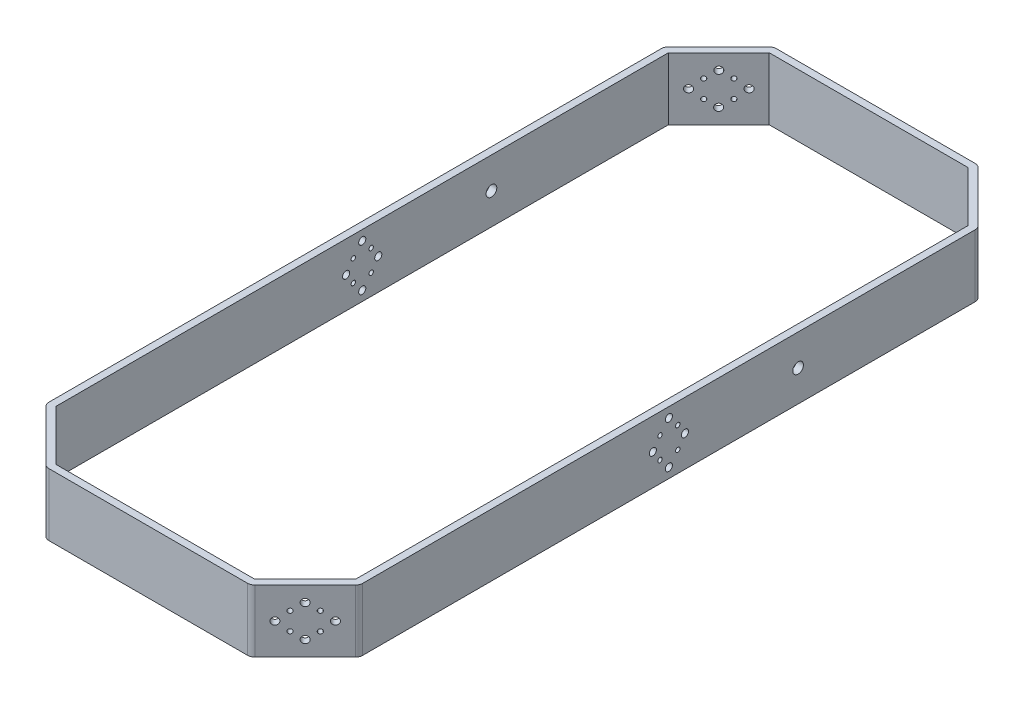
SolidWorks part; units mm, degrees
ref_plane "Ön Düzlem" through (0, 0, 0) normal (0, 0, 1) x (1, 0, 0)
ref_plane "Üst Düzlem" through (0, 0, 0) normal (0, 1, 0) x (1, 0, 0)
ref_plane "Sağ Düzlem" through (0, 0, 0) normal (1, 0, 0) x (0, 0, -1)
sketch "Çizim1" plane through (0, 0, 0) normal (0, 1, 0) x (1, 0, 0)
  line L1 (28.2843, 0) -> (139.7157, 0)
  line L2 (0, 28.2843) -> (0, 371.7157)
  line L3 (28.2843, 400) -> (139.7157, 400)
  line L4 (168, 28.2843) -> (168, 371.7157)
  line L5 (28.2843, 0) -> (0, 28.2843)
  line L6 (0, 371.7157) -> (28.2843, 400)
  line L7 (139.7157, 400) -> (168, 371.7157)
  line L8 (139.7157, 0) -> (168, 28.2843)
  line L9 (142.5442, -2.8284) -> (170.8284, 25.4558)
  line L12 (172, 28.2843) -> (172, 371.7157)
  line L15 (170.8284, 374.5442) -> (142.5442, 402.8284)
  line L18 (139.7157, 404) -> (28.2843, 404)
  line L21 (25.4558, 402.8284) -> (-2.8284, 374.5442)
  line L24 (-4, 371.7157) -> (-4, 28.2843)
  line L27 (-2.8284, 25.4558) -> (25.4558, -2.8284)
  line L30 (28.2843, -4) -> (139.7157, -4)
  arc A2 (25.4558, -2.8284) -> (28.2843, -4) centre (28.2843, 0) ccw
  arc A4 (139.7157, -4) -> (142.5442, -2.8284) centre (139.7157, 0) ccw
  arc A6 (170.8284, 25.4558) -> (172, 28.2843) centre (168, 28.2843) ccw
  arc A8 (172, 371.7157) -> (170.8284, 374.5442) centre (168, 371.7157) ccw
  arc A10 (142.5442, 402.8284) -> (139.7157, 404) centre (139.7157, 400) ccw
  arc A11 (28.2843, 404) -> (25.4558, 402.8284) centre (28.2843, 400) ccw
  arc A12 (-2.8284, 374.5442) -> (-4, 371.7157) centre (0, 371.7157) ccw
  arc A14 (-4, 28.2843) -> (-2.8284, 25.4558) centre (0, 28.2843) ccw
  dimension "D12" = 343.4315
  dimension "D16" = 4
  dimension "D18" = 4
  dimension "D19" = 4
  dimension "D21" = 4
  dimension "D26" = 4
  dimension "D27" = 4
  dimension "D2" = 28.2843
  dimension "D3" = 45
  dimension "D4" = 40
  dimension "D5" = 40
  dimension "D6" = 45
  dimension "D7" = 45
  dimension "D8" = 40
  dimension "D9" = 40
  dimension "D10" = 168
  dimension "D11" = 28.2843
  dimension "D13" = 343.4315
  dimension "D14" = 135
  dimension "D15" = 400
  dimension "D17" = 4
  dimension "D20" = 4
  dimension "D22" = 4
  dimension "D23" = 4
  dimension "D24" = 4
  dimension "D25" = 4
  dimension "D28" = 4
extrude "Yükseklik-Ekstrüzyon1" add sketch "Çizim1" along normal blind 35
sketch "Çizim2" plane through (172, 0, 0) normal (1, 0, 0) x (0, 0, -1)
  line L0 (371.7157, 35) -> (272.4683, 17.5)
  line L1 (28.2843, 0) -> (371.7157, 0)
  line L2 (28.2843, 0) -> (28.2843, 35)
  line L3 (28.2843, 35) -> (371.7157, 35)
  line L4 (371.7157, 0) -> (371.7157, 35)
  line L5 (272.4683, 17.5) -> (371.7157, 0)
  circle A0 centre (272.4683, 17.5) radius 3
  dimension "D3" = 6
  dimension "D1" = 10
  dimension "D2" = 10
extrude "Kes-Ekstrüzyon1" cut sketch "Çizim2" against normal blind 269 contours L5 A0 L0 | L0 A0 L5
sketch "Çizim3" plane through (272.6863, 0, -272.6863) normal (0.7071, 0, -0.7071) x (-0.7071, 0, -0.7071)
  circle A0 centre (176.0488, 17.5) radius 2
  circle A1 centre (164.0488, 8.5) radius 2
  circle A2 centre (164.0488, 26.5) radius 2
  circle A3 centre (152.0488, 17.5) radius 2
  circle A4 centre (158.0488, 22.5) radius 1.25
  circle A5 centre (170.0488, 22.4426) radius 1.25
  circle A6 centre (158.0488, 12.5) radius 1.25
  circle A7 centre (170.0488, 12.5574) radius 1.25
extrude "Kes-Ekstrüzyon2" cut sketch "Çizim3" against normal blind 10
sketch "Çizim4" plane through (-188.6863, 0, -188.6863) normal (-0.7071, 0, -0.7071) x (-0.7071, 0, 0.7071)
  circle A0 centre (-270.8427, 17.5) radius 2
  circle A1 centre (-282.8427, 26.5) radius 2
  circle A2 centre (-282.7736, 8.5) radius 2
  circle A3 centre (-294.8427, 17.5) radius 2
  circle A4 centre (-288.8427, 22.5) radius 1.25
  circle A5 centre (-276.8427, 22.5) radius 1.25
  circle A6 centre (-288.8427, 12.5) radius 1.25
  circle A7 centre (-276.8427, 12.5) radius 1.25
extrude "Kes-Ekstrüzyon3" cut sketch "Çizim4" against normal blind 10
sketch "Çizim5" plane through (11.3137, 0, -11.3137) normal (-0.7071, 0, 0.7071) x (0.7071, 0, 0.7071)
  circle A0 centre (6, 23.1463) radius 1.25
  circle A1 centre (-6, 23.1463) radius 1.25
  circle A2 centre (0, 27.1463) radius 2
  circle A3 centre (0, 8.5) radius 2
  circle A4 centre (6, 12.5) radius 1.25
  circle A5 centre (-6, 12.5) radius 1.25
  circle A6 centre (10.213, 17.5) radius 2
  circle A7 centre (-11.2453, 17.5) radius 2
extrude "Kes-Ekstrüzyon4" cut sketch "Çizim5" against normal blind 77
sketch "Çizim6" plane through (72.6863, 0, 72.6863) normal (0.7071, 0, 0.7071) x (0.7071, 0, -0.7071)
  circle A0 centre (124.7939, 12.5) radius 1.25
  circle A1 centre (112.7939, 12.5) radius 1.25
  circle A2 centre (112.7939, 22.5) radius 1.25
  circle A3 centre (118.7939, 26.5) radius 2
  circle A4 centre (124.7939, 22.5) radius 1.25
  circle A5 centre (130.7939, 17.5) radius 2
  circle A6 centre (106.7939, 17.5) radius 2
  circle A7 centre (118.7939, 8.5) radius 2
extrude "Kes-Ekstrüzyon5" cut sketch "Çizim6" against normal blind 77
sketch "Çizim7" plane through (172, 0, 0) normal (1, 0, 0) x (0, 0, -1)
  circle A0 centre (200, 26.5) radius 2
  circle A1 centre (194, 22.5) radius 1.25
  circle A2 centre (206, 22.5) radius 1.25
  circle A3 centre (194, 12.5) radius 1.25
  circle A4 centre (206, 12.5) radius 1.25
  circle A5 centre (200, 8.5) radius 2
  circle A6 centre (188, 17.5) radius 2
  circle A7 centre (212, 17.5) radius 2
extrude "Kes-Ekstrüzyon6" cut sketch "Çizim7" against normal blind 382
sketch "Çizim8" plane through (172, 0, 0) normal (1, 0, 0) x (0, 0, -1)
  circle A0 centre (200, 26.5) radius 2
  circle A1 centre (206, 22.5) radius 1.25
  circle A2 centre (194, 22.5) radius 1.25
  circle A3 centre (188, 17.5) radius 2
  circle A4 centre (194, 12.5) radius 1.25
  circle A5 centre (200, 8.5) radius 2
  circle A6 centre (206, 12.5) radius 1.25
  circle A7 centre (212, 17.5) radius 2
extrude "Yükseklik-Ekstrüzyon3" add sketch "Çizim8" against normal blind 4
sketch "Çizim9" plane through (-4, 0, 0) normal (-1, 0, 0) x (0, 0, 1)
  circle A0 centre (-200, 26.5) radius 2
  circle A1 centre (-194, 22.5) radius 1.25
  circle A2 centre (-206, 22.5) radius 1.25
  circle A3 centre (-212, 17.5) radius 2
  circle A4 centre (-206, 12.5) radius 1.25
  circle A5 centre (-200, 8.5) radius 2
  circle A6 centre (-194, 12.5) radius 1.25
  circle A7 centre (-188, 17.5) radius 2
extrude "Yükseklik-Ekstrüzyon4" add sketch "Çizim9" against normal blind 4
sketch "Çizim10" plane through (-4, 0, 0) normal (-1, 0, 0) x (0, 0, 1)
  circle A8 centre (-200, 29.5) radius 2
  circle A9 centre (-209, 17.5) radius 2
  circle A10 centre (-191, 17.5) radius 2
  circle A11 centre (-200, 5.5) radius 2
  circle A12 centre (-205, 23.5) radius 1.25
  circle A13 centre (-195, 23.5) radius 1.25
  circle A14 centre (-205, 11.5) radius 1.25
  circle A15 centre (-195, 11.5) radius 1.25
extrude "Kes-Ekstrüzyon8" cut sketch "Çizim10" against normal blind 228
